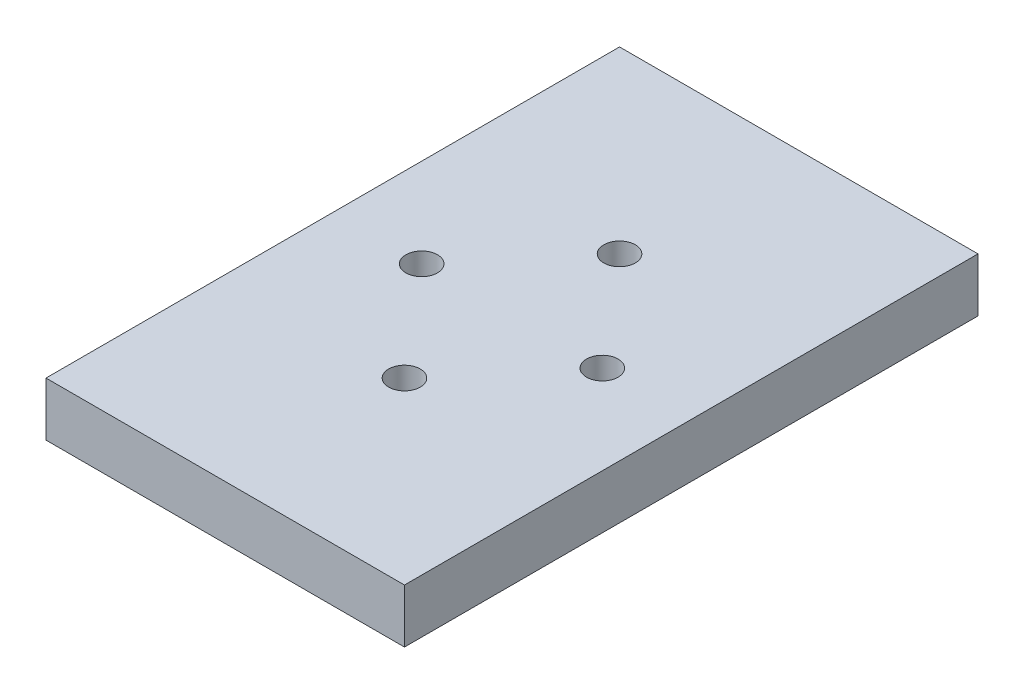
SolidWorks part; units mm, degrees
ref_plane "Front Plane" through (0, 0, 0) normal (0, 0, 1) x (1, 0, 0)
ref_plane "Top Plane" through (0, 0, 0) normal (0, 1, 0) x (1, 0, 0)
ref_plane "Right Plane" through (0, 0, 0) normal (1, 0, 0) x (0, 0, -1)
sketch "Sketch1" plane through (0, 0, 0) normal (0, 1, 0) x (1, 0, 0)
  line L0 (15.875, 15.875) -> (15.875, 25.4) construction
  line L1 (0, 0) -> (31.75, 0)
  line L2 (0, 0) -> (0, 50.8)
  line L3 (0, 50.8) -> (31.75, 50.8)
  line L4 (31.75, 0) -> (31.75, 50.8)
  line L5 (15.875, 25.4) -> (7.874, 25.4) construction
  line L6 (15.875, 25.4) -> (23.876, 25.4) construction
  line L7 (15.875, 25.4) -> (15.875, 34.925) construction
  circle A0 centre (7.874, 25.4) radius 1.397
  circle A1 centre (15.875, 34.925) radius 1.397
  circle A2 centre (23.876, 25.4) radius 1.397
  circle A3 centre (15.875, 15.875) radius 1.397
  dimension "D1" = 2.794
  dimension "D2" = 16.002
  dimension "D3" = 19.05
  dimension "D4" = 50.8
  dimension "D5" = 31.75
  dimension "D6" = 25.4
  dimension "D7" = 15.875
extrude "Boss-Extrude1" add sketch "Sketch1" along normal blind 4.7625
